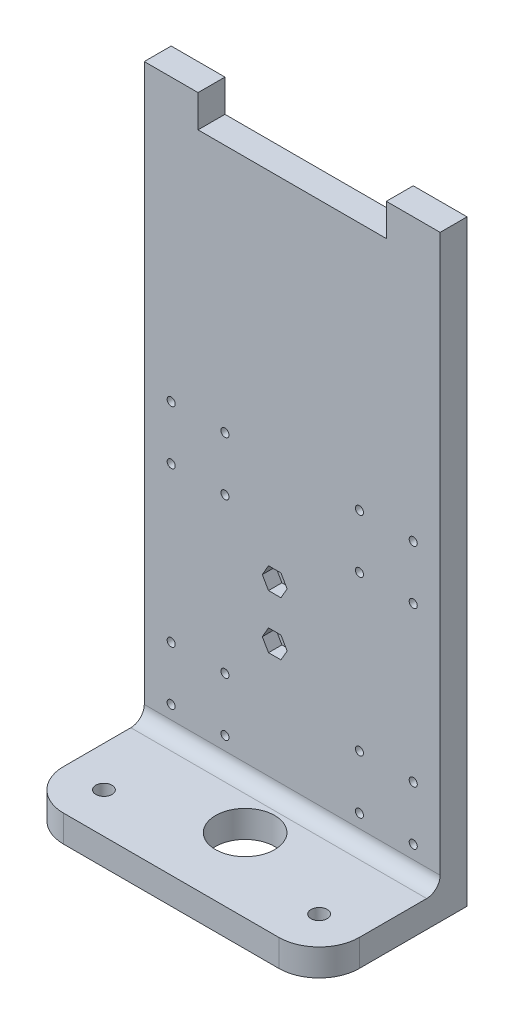
SolidWorks part; units mm, degrees
other "Markup1"
sketch "Sketch5" plane through (110, 210, 50) normal (0.5774, 0.5773, 0.5774) x (0.7071, 0, -0.7071)
ref_plane "Front Plane" through (0, 0, 0) normal (0, 0, 1) x (1, 0, 0)
ref_plane "Top Plane" through (0, 0, 0) normal (0, 1, 0) x (1, 0, 0)
ref_plane "Right Plane" through (0, 0, 0) normal (1, 0, 0) x (0, 0, -1)
sketch "Sketch1" plane through (0, 0, 0) normal (0, 0, 1) x (1, 0, 0)
  line L0 (55, 0) -> (55, 87.4837) construction
  line L1 (20, 0) -> (90, 0)
  line L2 (0, 0) -> (0, 200)
  line L3 (20, 200) -> (90, 200)
  line L4 (110, 0) -> (110, 200)
  line L5 (80, 20) -> (109.7449, 20) construction
  line L6 (2.5973, 58.75) -> (109.7449, 58.75) construction
  line L7 (20, 0) -> (0, 0)
  line L8 (0, -12) -> (20, -12) construction
  line L9 (20, -12) -> (20, 0) construction
  line L10 (0, 100) -> (110, 100) construction
  line L11 (0, -12) -> (0, 0) construction
  line L12 (110, -12) -> (90, -12) construction
  line L13 (90, -12) -> (90, 0) construction
  line L14 (110, 0) -> (110, -12) construction
  line L15 (110, 200) -> (110, 212)
  line L16 (110, 212) -> (90, 212)
  line L17 (90, 212) -> (90, 200)
  line L18 (0, 200) -> (0, 212)
  line L19 (20, 212) -> (20, 200)
  line L20 (0, 212) -> (20, 212)
  line L21 (90, 0) -> (110, 0)
  circle A0 centre (100, 10) radius 1.5
  circle A1 centre (80, 10) radius 1.5
  circle A2 centre (100, 30) radius 1.5
  circle A3 centre (80, 30) radius 1.5
  circle A4 centre (30, 10) radius 1.5
  circle A5 centre (10, 10) radius 1.5
  circle A6 centre (10, 30) radius 1.5
  circle A7 centre (30, 30) radius 1.5
  circle A8 centre (100, 107.5) radius 1.5
  circle A9 centre (100, 87.5) radius 1.5
  circle A10 centre (80, 87.5) radius 1.5
  circle A11 centre (80, 107.5) radius 1.5
  circle A12 centre (30, 107.5) radius 1.5
  circle A13 centre (10, 107.5) radius 1.5
  circle A14 centre (30, 87.5) radius 1.5
  circle A15 centre (10, 87.5) radius 1.5
  circle A16 centre (48.5, 68.75) radius 2.5
  circle A17 centre (48.5, 48.75) radius 2.5
  point P61 (0, 0)
  point P66 (40, 25)
  dimension "D3" = 3
  dimension "D11" = 5
  dimension "D1" = 110
  dimension "D2" = 200
  dimension "D4" = 20
  dimension "D5" = 10
  dimension "D6" = 10
  dimension "D7" = 10
  dimension "D8" = 38.75
  dimension "D9" = 20
  dimension "D10" = 12
  dimension "D12" = 20
  dimension "D13" = 10
  dimension "D14" = 6.5
extrude "Boss-Extrude1" add sketch "Sketch1" along normal blind 10
sketch "Sketch4" plane through (0, 0, 0) normal (0, 0, -1) x (-1, 0, 0)
  line L1 (0, 0) -> (-110, 0)
  line L2 (0, 0) -> (0, -10)
  line L3 (0, -10) -> (-110, -10)
  line L4 (-110, 0) -> (-110, -10)
  dimension "D1" = 110
  dimension "D2" = 10
extrude "Boss-Extrude2" add sketch "Sketch4" against normal blind 55
sketch "Sketch6" plane through (0, 0, 0) normal (0, 1, 0) x (1, 0, 0)
  line L1 (0, -55) -> (0, -10) construction
  line L3 (110, -55) -> (110, -10) construction
  line L4 (0, -55) -> (110, -55) construction
  line L5 (0, -10) -> (110, -10) construction
  circle A0 centre (95, -40) radius 3
  circle A1 centre (15, -40) radius 3
  circle A2 centre (55, -27.5) radius 11
  dimension "D1" = 6
  dimension "D7" = 22
  dimension "D2" = 15
  dimension "D3" = 15
  dimension "D4" = 15
  dimension "D5" = 15
  dimension "D6" = 55
  dimension "D8" = 17.5
extrude "Cut-Extrude1" cut sketch "Sketch6" against normal through all
fillet "Fillet1" radius 5 1 edges at (55, 0, 10)
fillet "Fillet2" radius 15 2 edges at (110, -5, 55) (0, -5, 55)
sketch "Sketch7" plane through (0, 0, 10) normal (0, 0, 1) x (1, 0, 0)
  line L1 (46.1906, 72.75) -> (43.8812, 68.75)
  line L2 (43.8812, 68.75) -> (46.1906, 64.75)
  line L3 (46.1906, 64.75) -> (50.8094, 64.75)
  line L4 (50.8094, 64.75) -> (53.1188, 68.75)
  line L5 (53.1188, 68.75) -> (50.8094, 72.75)
  line L6 (50.8094, 72.75) -> (46.1906, 72.75)
  line L7 (50.8094, 52.75) -> (46.1906, 52.75)
  line L8 (46.1906, 52.75) -> (43.8812, 48.75)
  line L9 (43.8812, 48.75) -> (46.1906, 44.75)
  line L10 (46.1906, 44.75) -> (50.8094, 44.75)
  line L11 (50.8094, 44.75) -> (53.1188, 48.75)
  line L12 (53.1188, 48.75) -> (50.8094, 52.75)
  circle A0 centre (48.5, 68.75) radius 4 construction
  circle A1 centre (48.5, 48.75) radius 4 construction
  dimension "D1" = 8
extrude "Cut-Extrude2" cut sketch "Sketch7" against normal blind 5
sketch "Sketch9" plane through (0, 0, 0) normal (0, 0, -1) x (-1, 0, 0)
  line L0 (-2.5973, 58.75) -> (-109.7449, 58.75) construction
  line L1 (-37.5, 76.25) -> (-72.5, 76.25)
  line L2 (-37.5, 76.25) -> (-37.5, 41.25)
  line L3 (-37.5, 41.25) -> (-72.5, 41.25)
  line L4 (-72.5, 76.25) -> (-72.5, 41.25)
  line L5 (-55, 0) -> (-55, 87.4837) construction
  circle A0 centre (-48.5, 48.75) radius 2.5 construction
  circle A1 centre (-48.5, 68.75) radius 2.5 construction
  circle A2 centre (-48.5, 48.75) radius 2.5
  circle A3 centre (-48.5, 68.75) radius 2.5
  dimension "D1" = 17.5
  dimension "D2" = 35
  dimension "D3" = 35
  dimension "D4" = 17.5
extrude "Boss-Extrude3" [suppressed] add sketch "Sketch9" along normal blind 12
